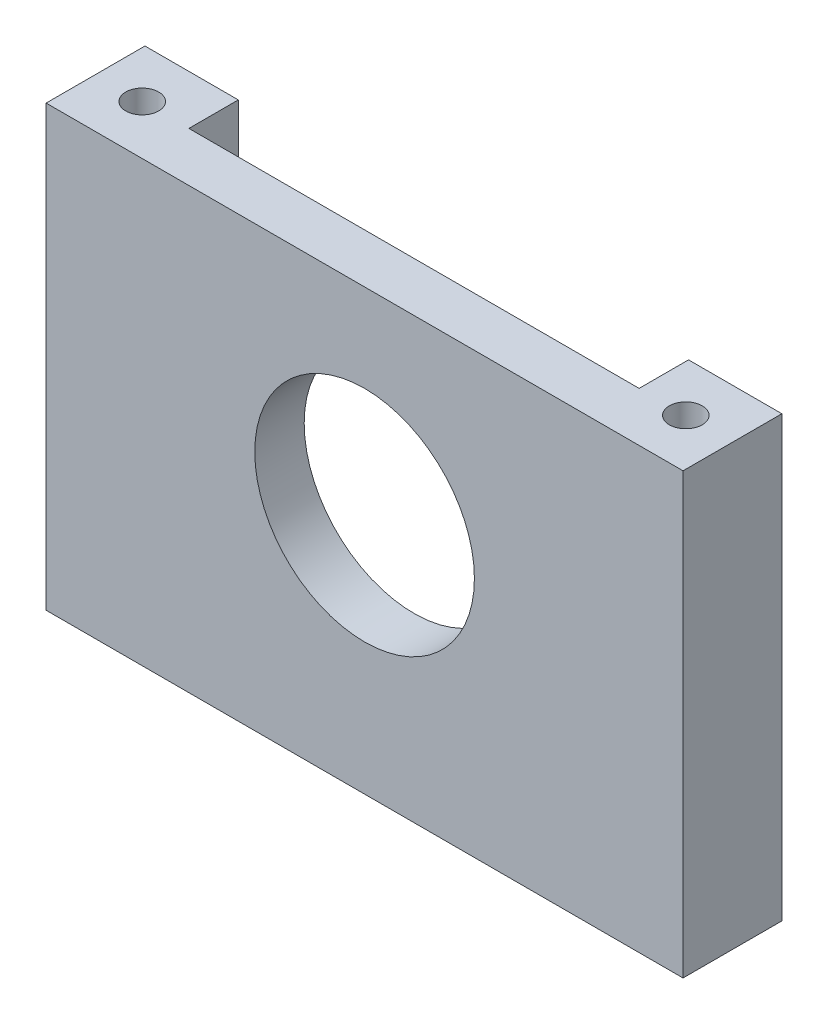
SolidWorks part; units mm, degrees
ref_plane "Front Plane" through (0, 0, 0) normal (0, 0, 1) x (1, 0, 0)
ref_plane "Top Plane" through (0, 0, 0) normal (0, 1, 0) x (1, 0, 0)
ref_plane "Right Plane" through (0, 0, 0) normal (1, 0, 0) x (0, 0, -1)
sketch "Sketch1" plane through (0, 0, 0) normal (0, 0, 1) x (1, 0, 0)
  line L1 (-29, 20) -> (29, 20)
  line L2 (-29, 20) -> (-29, -20)
  line L3 (-29, -20) -> (29, -20)
  line L4 (29, 20) -> (29, -20)
  line L5 (-29, 20) -> (29, -20) construction
  line L6 (-29, -20) -> (29, 20) construction
  circle A0 centre (0, 2) radius 10
  point P0 (0, 0)
  dimension "D3" = 20
  dimension "D5" = 29
  dimension "D1" = 40
  dimension "D2" = 58
  dimension "D4" = 22
extrude "Boss-Extrude1" add sketch "Sketch1" along normal blind 9
sketch "Sketch2" plane through (0, 0, 0) normal (0, 0, -1) x (-1, 0, 0)
  line L0 (29, -20) -> (-29, -20) construction
  line L1 (-20.5, 20) -> (20.5, 20)
  line L2 (-20.5, 20) -> (-20.5, -20)
  line L3 (-20.5, -20) -> (20.5, -20)
  line L4 (20.5, 20) -> (20.5, -20)
  line L5 (-20.5, 20) -> (20.5, -20) construction
  line L6 (-20.5, -20) -> (20.5, 20) construction
  point P1 (0, 0)
  dimension "D1" = 41
extrude "Cut-Extrude1" cut sketch "Sketch2" against normal blind 4.5
sketch "Sketch3" plane through (0, 20, 0) normal (0, 1, 0) x (1, 0, 0)
  line L1 (20.5, -4.5) -> (20.5, 0) construction
  line L2 (29, 0) -> (20.5, 0) construction
  line L3 (-20.5, 0) -> (-29, 0) construction
  line L4 (-20.5, -4.5) -> (-20.5, 0) construction
  circle A0 centre (24.75, -4.5) radius 1.5
  circle A1 centre (-24.75, -4.5) radius 1.5
  point P7 (24.75, 0)
  point P13 (-24.75, 0)
  dimension "D1" = 3
  dimension "D2" = 4.25
  dimension "D3" = 4.5
  dimension "D5" = 3
  dimension "D6" = 4.25
  dimension "D4" = 4.5
extrude "Cut-Extrude2" cut sketch "Sketch3" against normal through all
